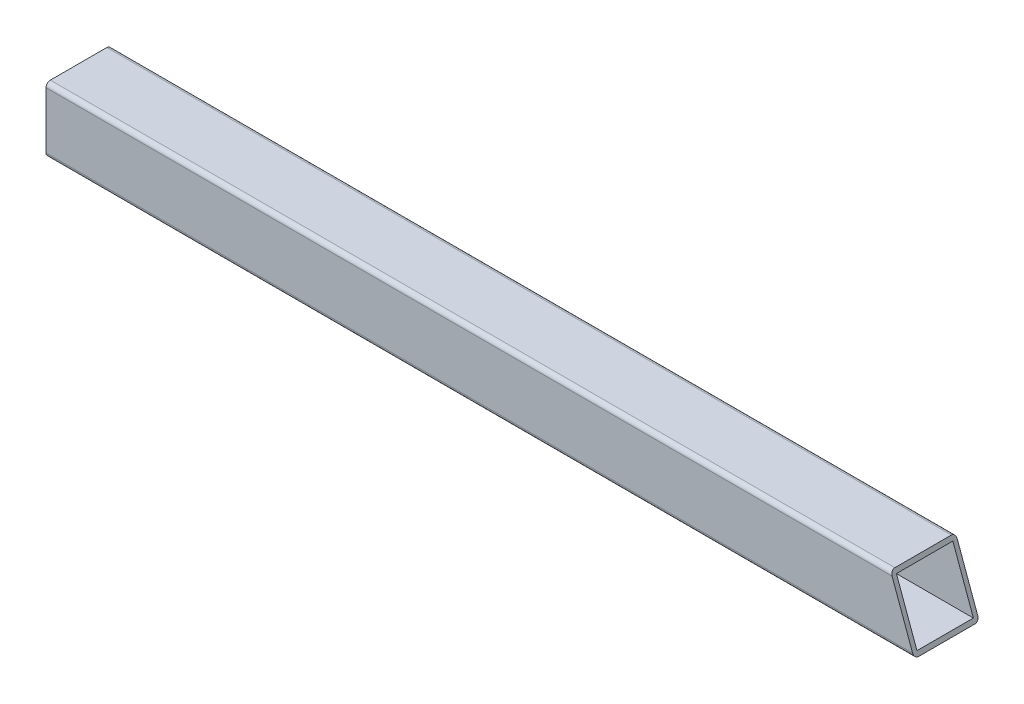
SolidWorks part; units mm, degrees
ref_plane "Front Plane" through (0, 0, 0) normal (0, 0, 1) x (1, 0, 0)
ref_plane "Top Plane" through (0, 0, 0) normal (0, 1, 0) x (1, 0, 0)
ref_plane "Right Plane" through (0, 0, 0) normal (1, 0, 0) x (0, 0, -1)
sketch "Sketch1" plane through (0, 0, 0) normal (1, 0, 0) x (0, 0, -1)
  line L0 (10, 10) -> (10, 140)
  line L1 (10, 0) -> (140, 0)
  line L2 (0, 10) -> (0, 140)
  line L3 (10, 150) -> (140, 150)
  line L4 (150, 10) -> (150, 140)
  line L5 (10, 10) -> (140, 10)
  line L6 (140, 10) -> (140, 140)
  line L7 (10, 140) -> (140, 140)
  arc A0 (0, 140) -> (10, 150) centre (10, 140) cw
  arc A1 (150, 140) -> (140, 150) centre (140, 140) ccw
  arc A2 (10, 0) -> (0, 10) centre (10, 10) cw
  arc A3 (140, 0) -> (150, 10) centre (140, 10) ccw
  point P6 (0, 150)
  point P9 (150, 150)
  point P12 (0, 0)
  dimension "D3" = 10
  dimension "Width" = 150
  dimension "D2" = 150
extrude "Extrude1" add sketch "Sketch1" along normal blind 2000
sketch "Sketch2" plane through (0, 0, 0) normal (0, 0, 1) x (1, 0, 0)
  line L0 (2000, 0) -> (1945.4045, 150)
  line L1 (2000, 150) -> (0, 150) construction
  line L2 (2000, 0) -> (0, 0) construction
  dimension "D1" = 70
extrude "Cut-Extrude2" cut sketch "Sketch2" against normal through all and the other way through all flip side to cut
